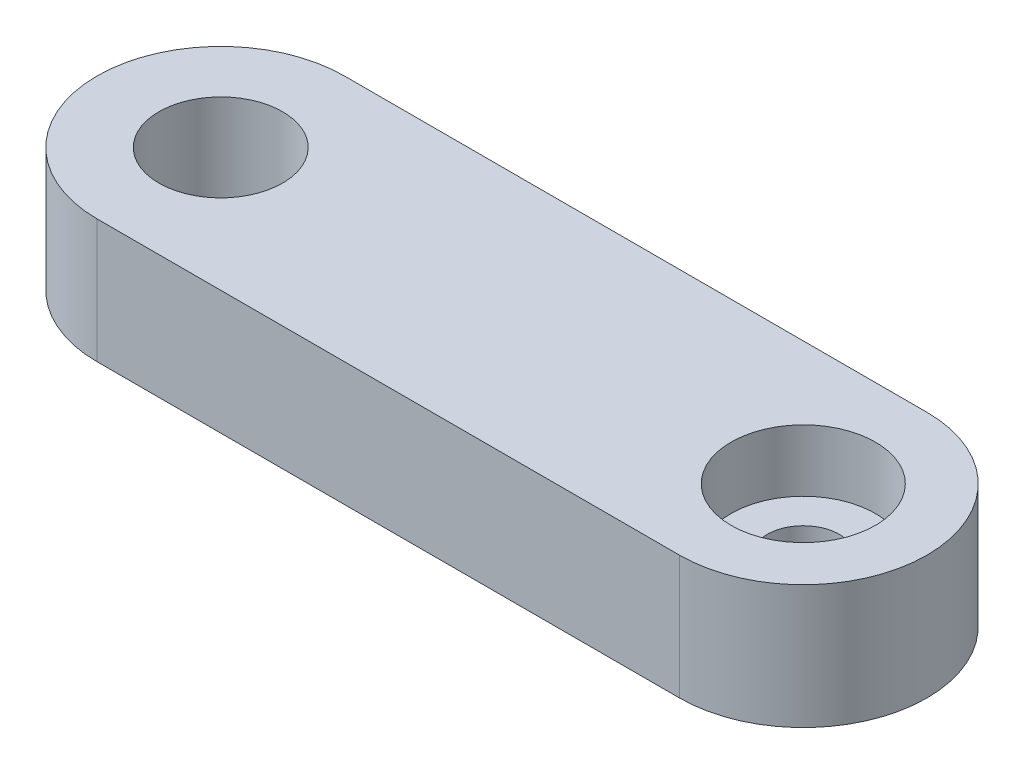
SolidWorks part; units mm, degrees
material "3D printed plastic"
ref_plane "Front Plane" through (0, 0, 0) normal (0, 0, 1) x (1, 0, 0)
ref_plane "Top Plane" through (0, 0, 0) normal (0, 1, 0) x (1, 0, 0)
ref_plane "Right Plane" through (0, 0, 0) normal (1, 0, 0) x (0, 0, -1)
sketch "Sketch1" plane through (0, 0, 0) normal (0, 1, 0) x (1, 0, 0)
  line L0 (0, 0) -> (-28.25, 0) construction
  line L1 (0, -6) -> (-28.25, -6)
  line L2 (0, 6) -> (-28.25, 6)
  circle A0 centre (0, 0) radius 1.75
  circle A1 centre (-28.25, 0) radius 3
  arc A2 (0, -6) -> (0, 6) centre (0, 0) ccw
  arc A3 (-28.25, 6) -> (-28.25, -6) centre (-28.25, 0) ccw
  point P5 (-14.125, 0)
  dimension "D1" = 28.25
  dimension "D2" = 0
  dimension "D3" = 3.5
  dimension "D5" = 6
  dimension "D4" = 12
extrude "Boss-Extrude1" add sketch "Sketch1" along normal blind 6
sketch "Sketch2" plane through (0, 6, 0) normal (0, 1, 0) x (1, 0, 0)
  circle A0 centre (0, 0) radius 3.5
  dimension "D1" = 7
extrude "Cut-Extrude1" cut sketch "Sketch2" against normal blind 3
